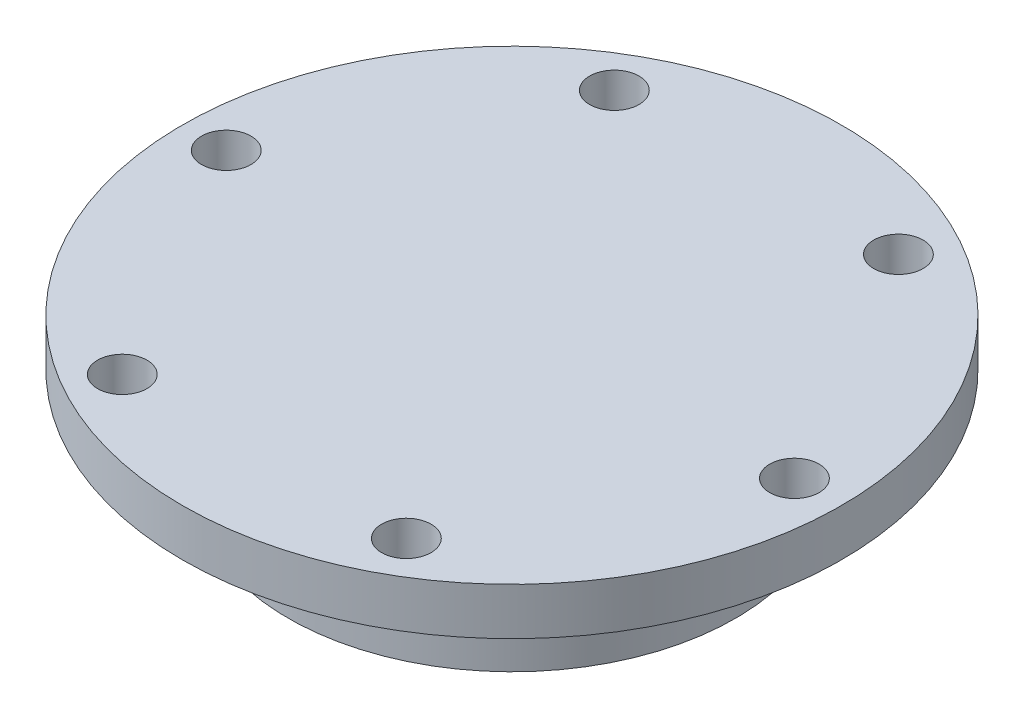
SolidWorks part; units mm, degrees
ref_plane "Alzado" through (0, 0, 0) normal (0, 0, 1) x (1, 0, 0)
ref_plane "Planta" through (0, 0, 0) normal (0, 1, 0) x (1, 0, 0)
ref_plane "Vista lateral" through (0, 0, 0) normal (1, 0, 0) x (0, 0, -1)
sketch "Croquis1" plane through (0, 0, 0) normal (0, 1, 0) x (1, 0, 0)
  circle A0 centre (0, 0) radius 70
  dimension "D1" = 140
extrude "Saliente-Extruir1" add sketch "Croquis1" along normal blind 10
sketch "Croquis2" plane through (0, 10, 0) normal (0, 1, 0) x (1, 0, 0)
  circle A0 centre (0, 0) radius 60
  dimension "D1" = 120
sketch "Croquis4" plane through (0, 0, 0) normal (0, -1, 0) x (-1, 0, 0)
  circle A1 centre (0, 0) radius 47.5
  dimension "D1" = 95
extrude "Saliente-Extruir2" add sketch "Croquis4" along normal blind 22
sketch "Croquis5" plane through (0, 10, 0) normal (0, 1, 0) x (1, 0, 0)
  line L0 (0, 0) -> (60, 0)
  circle A0 centre (0, 0) radius 60 construction
hole_wizard "Perforador para roscar para macho de roscar para M12x1.51" positions "Croquis3D1" profile "Croquis6" hole size "M12x1.5" standard "Ansi Metric"
sketch3d "Croquis3D1"
  line L0 (0, 10, 0) -> (60, 10, 0) construction
  circle A0 centre (0, 10, 0) radius 60 construction
  point P0 (60, 10, 0)
  point P4 (0, 70, 0)
sketch "Croquis6" plane through (60, 10, 0) normal (1, 0, 0) x (0, 0, 1)
  line L0 (0, 0) -> (0, 46.6545)
  line L1 (0, 46.6545) -> (5.25, 43.5)
  line L2 (5.25, 43.5) -> (5.25, 0)
  line L5 (5.25, 0) -> (0, 0)
  line L10 (0, 46.6545) -> (-5.25, 43.5) construction
  line L11 (0, -6.35) -> (0, 107.95) construction
  dimension "Diámetro de taladro" = 10.5
  dimension "Profundidad de taladro" = 43.5
  dimension "Ángulo de perforador" = 118
pattern_circular "MatrizC1" count 6 over 360 about axis through (-0.3394, 0, 0) along (0, 1, 0) of "Perforador para roscar para macho de roscar para M12x1.51"
